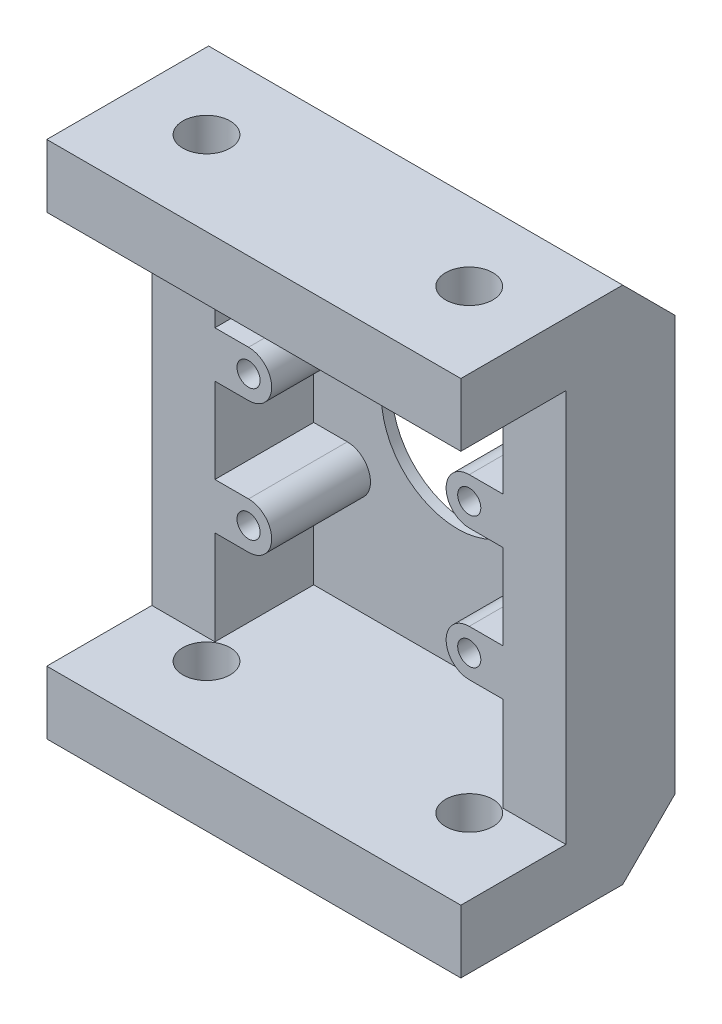
SolidWorks part; units mm, degrees
ref_plane "Front Plane" through (0, 0, 0) normal (0, 0, 1) x (1, 0, 0)
ref_plane "Top Plane" through (0, 0, 0) normal (0, 1, 0) x (1, 0, 0)
ref_plane "Right Plane" through (0, 0, 0) normal (1, 0, 0) x (0, 0, -1)
sketch "Sketch1" plane through (0, 0, 0) normal (0, 0, 1) x (1, 0, 0)
  line L0 (-19.7, -24.7) -> (-19.7, 24.7)
  line L1 (20, -25) -> (-20, -25) construction
  line L2 (20, -25) -> (20, 25) construction
  line L3 (20, 25) -> (-20, 25) construction
  line L4 (-20, -25) -> (-20, 25) construction
  line L5 (20, -25) -> (-20, 25) construction
  line L6 (20, 25) -> (-20, -25) construction
  line L7 (19.7, 24.7) -> (-19.7, 24.7)
  line L8 (19.7, -24.7) -> (19.7, 24.7)
  line L9 (19.7, -24.7) -> (-19.7, -24.7)
  point P0 (0, 0)
  dimension "D1" = 50
  dimension "D2" = 40
  dimension "D3" = 0.3
extrude "Boss-Extrude1" add sketch "Sketch1" along normal blind 1
sketch "Sketch2" plane through (0, 0, 1) normal (0, 0, 1) x (1, 0, 0)
  circle A0 centre (0, 0) radius 7.25
  dimension "D1" = 14.5
extrude "Cut-Extrude1" cut sketch "Sketch2" against normal through all
sketch "Sketch3" plane through (0, 0, 1) normal (0, 0, 1) x (1, 0, 0)
  line L0 (10.5, 4.98) -> (10.5, 0) construction
  line L1 (10.5, 0) -> (0, 0) construction
  line L2 (-10.5, 4.98) -> (-10.5, 0) construction
  line L3 (-10.5, 0) -> (0, 0) construction
  line L4 (-10.5, 0) -> (-10.5, -7.52) construction
  line L5 (10.5, 0) -> (10.5, -7.52) construction
  circle A0 centre (-10.5, 4.98) radius 1
  circle A1 centre (10.5, 4.98) radius 1
  circle A2 centre (-10.5, -7.52) radius 1
  circle A3 centre (10.5, -7.52) radius 1
  circle A4 centre (-10.5, 4.98) radius 2.2
  circle A5 centre (-10.5, -7.52) radius 2.2
  circle A6 centre (10.5, -7.52) radius 2.2
  circle A7 centre (10.5, 4.98) radius 2.2
  dimension "D4" = 2
  dimension "D5" = 1.2
  dimension "D1" = 10.5
  dimension "D2" = 4.98
  dimension "D3" = 7.52
extrude "Boss-Extrude2" add sketch "Sketch3" along normal blind 10.4 from surface at -1 starting at face at (7.25, 0, 0)
sketch "Sketch4" plane through (0, 0, 1) normal (0, 0, 1) x (1, 0, 0)
  line L0 (19.7, -24.7) -> (19.7, 24.7) construction
  line L1 (-19.7, -24.7) -> (19.7, -24.7) construction
  line L2 (19.7, 24.7) -> (-19.7, 24.7) construction
  line L3 (-19.7, 24.7) -> (-19.7, -24.7) construction
  line L4 (19.7, -24.7) -> (19.7, 24.7)
  line L5 (-19.7, -24.7) -> (19.7, -24.7)
  line L6 (19.7, 24.7) -> (-19.7, 24.7)
  line L7 (-19.7, 24.7) -> (-19.7, -24.7)
  line L8 (-13.7, 18.7) -> (-13.7, -18.7)
  line L9 (-13.7, -18.7) -> (13.7, -18.7)
  line L10 (13.7, -18.7) -> (13.7, 18.7)
  line L11 (13.7, 18.7) -> (-13.7, 18.7)
  dimension "D1" = 6
extrude "Boss-Extrude4" add sketch "Sketch4" along normal up to surface (9.4 mm away) up to face at (-11.5, 4.98, 10.4)
sketch "Sketch5" plane through (0, 0, 10.4) normal (0, 0, 1) x (1, 0, 0)
  line L0 (19.7, 24.7) -> (19.7, -24.7) construction
  line L1 (-19.7, 24.7) -> (19.7, 24.7)
  line L2 (-19.7, 24.7) -> (-19.7, 18.7)
  line L3 (-19.7, 18.7) -> (19.7, 18.7)
  line L4 (19.7, 24.7) -> (19.7, 18.7)
  line L5 (-19.7, -24.7) -> (-19.7, 24.7) construction
  line L6 (19.7, -24.7) -> (-19.7, -24.7)
  line L7 (19.7, -24.7) -> (19.7, -18.7)
  line L8 (19.7, -18.7) -> (-19.7, -18.7)
  line L9 (-19.7, -24.7) -> (-19.7, -18.7)
  line L10 (-13.7, 18.7) -> (13.7, 18.7) construction
  line L11 (-13.7, -18.7) -> (13.7, -18.7) construction
extrude "Boss-Extrude5" add sketch "Sketch5" along normal blind 10
sketch "Sketch6" plane through (0, 24.7, 0) normal (0, 1, 0) x (1, 0, 0)
  circle A0 centre (-12.5, -12.4) radius 1.65 construction
  circle A1 centre (12.5, -12.4) radius 1.65 construction
  circle A2 centre (-12.5, -12.4) radius 1.65
  circle A3 centre (12.5, -12.4) radius 1.65
extrude "Cut-Extrude3" cut sketch "Sketch6" against normal through all
sketch "Sketch7" plane through (0, 24.7, 0) normal (0, 1, 0) x (1, 0, 0)
  circle A0 centre (12.5, -12.4) radius 2.25
  circle A1 centre (-12.5, -12.4) radius 2.25
  dimension "D1" = 4.5
extrude "Cut-Extrude4" cut sketch "Sketch7" against normal through all
sketch "Sketch8" plane through (0, 0, 10.4) normal (0, 0, 1) x (1, 0, 0)
  line L0 (-10.5, 7.18) -> (-13.7, 7.18)
  line L1 (-13.7, -18.7) -> (-13.7, 18.7) construction
  line L2 (-10.5, 2.78) -> (-13.7, 2.78)
  line L3 (-13.7, 18.7) -> (-13.7, -18.7) construction
  line L4 (-10.5, -5.32) -> (-13.7, -5.32)
  line L5 (10.5, 7.18) -> (13.7, 7.18)
  line L6 (13.7, -18.7) -> (13.7, 18.7) construction
  line L7 (13.7, 7.18) -> (13.7, 2.78)
  line L8 (13.7, 2.78) -> (10.5, 2.78)
  line L9 (-10.5, -9.72) -> (-13.7, -9.72)
  line L10 (-13.7, -9.72) -> (-13.7, -5.32)
  line L11 (10.5, -5.32) -> (13.7, -5.32)
  line L12 (13.7, -5.32) -> (13.7, -9.72)
  line L13 (13.7, -9.72) -> (10.5, -9.72)
  line L14 (-13.7, 7.18) -> (-13.7, 2.78)
  circle A0 centre (-10.5, 4.98) radius 2.2 construction
  circle A1 centre (-10.5, 4.98) radius 2.2 construction
  circle A2 centre (-10.5, -7.52) radius 2.2 construction
  circle A3 centre (-10.5, -7.52) radius 2.2 construction
  circle A4 centre (10.5, 4.98) radius 2.2 construction
  arc A5 (11.4692, 6.955) -> (11.4692, 3.005) centre (10.5, 4.98) ccw construction
  arc A7 (11.4692, -5.545) -> (11.4692, -9.495) centre (10.5, -7.52) ccw construction
  circle A8 centre (10.5, -7.52) radius 2.2 construction
  arc A12 (-10.5, 7.18) -> (-10.5, 2.78) centre (-10.5, 4.98) cw
  arc A13 (10.5, 7.18) -> (10.5, 2.78) centre (10.5, 4.98) ccw
  arc A14 (10.5, -5.32) -> (10.5, -9.72) centre (10.5, -7.52) ccw
  arc A15 (-10.5, -5.32) -> (-10.5, -9.72) centre (-10.5, -7.52) cw
extrude "Boss-Extrude6" add sketch "Sketch8" against normal up to surface (9.4 mm away) up to face at (0, 0, 1)
sketch "Sketch9" plane through (0, 0, 10.4) normal (0, 0, 1) x (1, 0, 0)
  circle A0 centre (-10.5, 4.98) radius 1.1
  circle A1 centre (10.5, 4.98) radius 1.1
  circle A2 centre (10.5, -7.52) radius 1.1
  circle A3 centre (-10.5, -7.52) radius 1.1
  arc A4 (-10.5, -9.72) -> (-10.5, -5.32) centre (-10.5, -7.52) ccw construction
  arc A5 (-10.5, 2.78) -> (-10.5, 7.18) centre (-10.5, 4.98) ccw construction
  arc A6 (10.5, 7.18) -> (10.5, 2.78) centre (10.5, 4.98) ccw construction
  arc A7 (10.5, -5.32) -> (10.5, -9.72) centre (10.5, -7.52) ccw construction
  dimension "D1" = 2.2
extrude "Cut-Extrude5" cut sketch "Sketch9" against normal blind 8 draft 2
chamfer "Chamfer1" distance 5 angle 45 2 edges at (0, -24.7, 0) (0, 24.7, 0)
